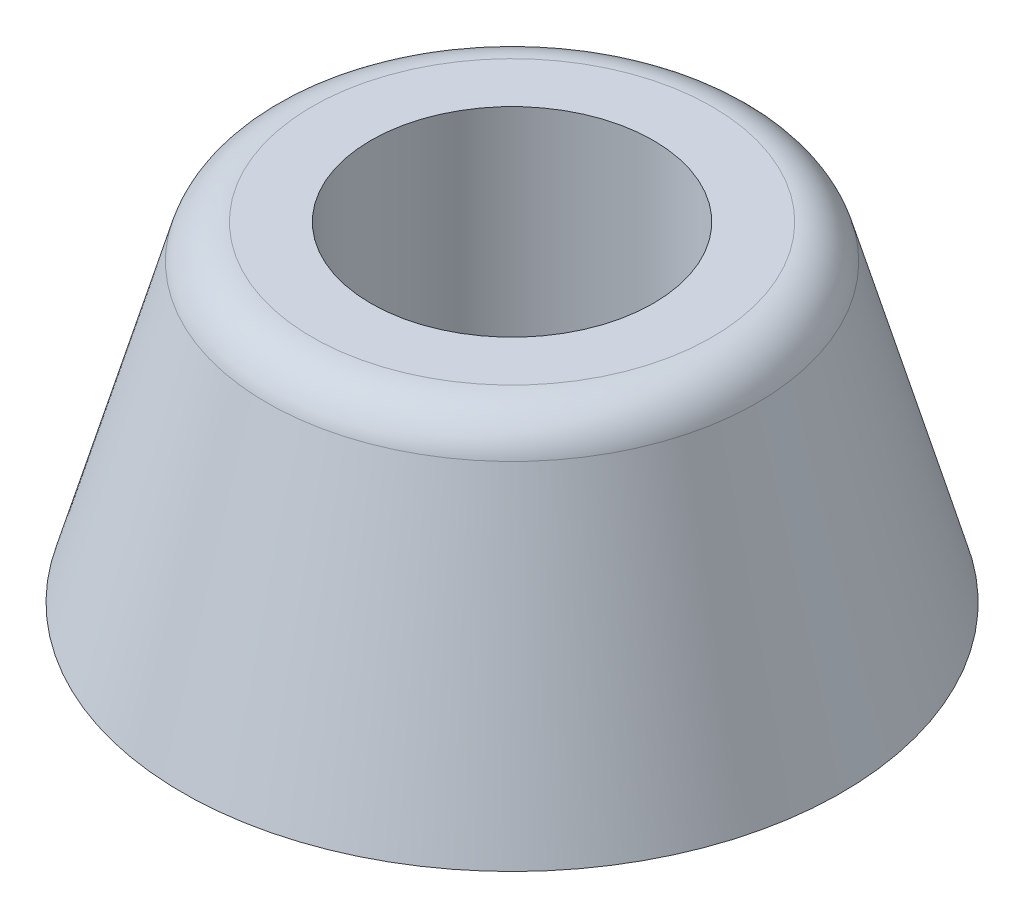
SolidWorks part; units mm, degrees
material "Caucho de silicio"
ref_plane "Alzado" through (0, 0, 0) normal (0, 0, 1) x (1, 0, 0)
ref_plane "Planta" through (0, 0, 0) normal (0, 1, 0) x (1, 0, 0)
ref_plane "Vista lateral" through (0, 0, 0) normal (1, 0, 0) x (0, 0, -1)
sketch "Croquis1" plane through (0, 0, 0) normal (0, 0, 1) x (1, 0, 0)
  line L0 (0, 0) -> (0, 7) construction
  line L1 (-7, 0) -> (-1.5, 0)
  line L2 (-3, 7) -> (-4.2457, 7)
  line L3 (-5.2072, 6.2747) -> (-7, 0)
  line L4 (-1.5, 0) -> (-1.5, 2)
  line L5 (-1.5, 2) -> (-3, 2)
  line L6 (-3, 2) -> (-3, 7)
  arc A0 (-4.2457, 7) -> (-5.2072, 6.2747) centre (-4.2457, 6) ccw
  point P7 (-5, 7)
  point P8 (-1.5, 0)
  dimension "D2" = 7
  dimension "D4" = 1
  dimension "D7" = 1.5
  dimension "D1" = 7
  dimension "D3" = 5
  dimension "D5" = 1.5
  dimension "D6" = 2
revolve "Revolución1" add sketch "Croquis1" angle 360 about L0
